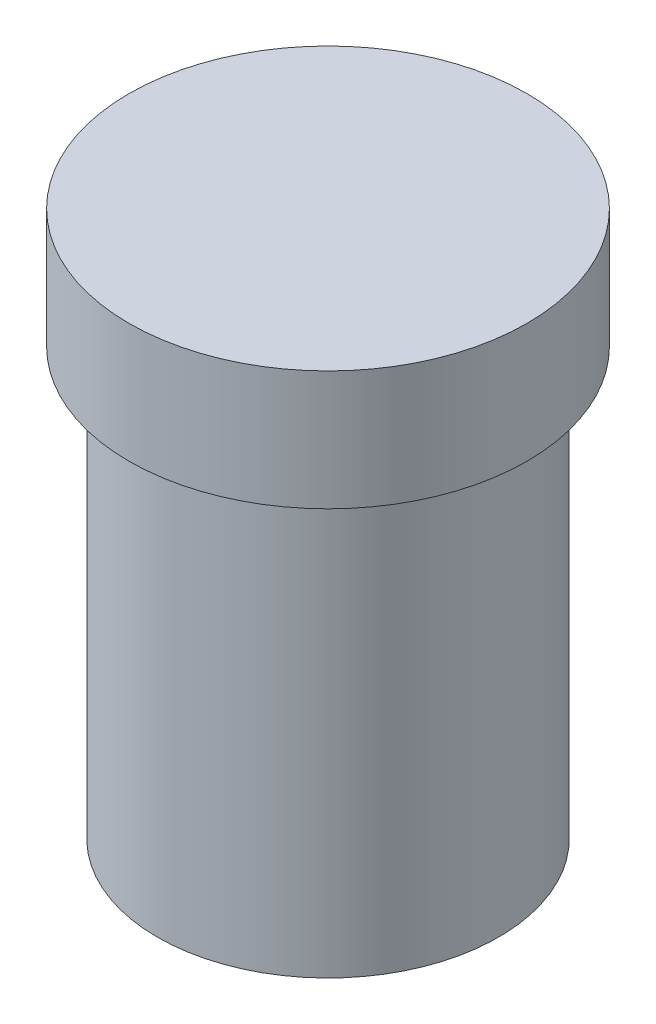
SolidWorks part; units mm, degrees
ref_plane "Front Plane" through (0, 0, 0) normal (0, 0, 1) x (1, 0, 0)
ref_plane "Top Plane" through (0, 0, 0) normal (0, 1, 0) x (1, 0, 0)
ref_plane "Right Plane" through (0, 0, 0) normal (1, 0, 0) x (0, 0, -1)
sketch "Sketch1" plane through (0, 0, 0) normal (0, 1, 0) x (1, 0, 0)
  circle A0 centre (0, 0) radius 6
  dimension "D1" = 12
extrude "Boss-Extrude1" add sketch "Sketch1" along normal blind 15
sketch "Sketch2" plane through (0, 15, 0) normal (0, 1, 0) x (1, 0, 0)
  circle A0 centre (0, 0) radius 7
  dimension "D1" = 14
extrude "Boss-Extrude2" add sketch "Sketch2" along normal blind 4.2
